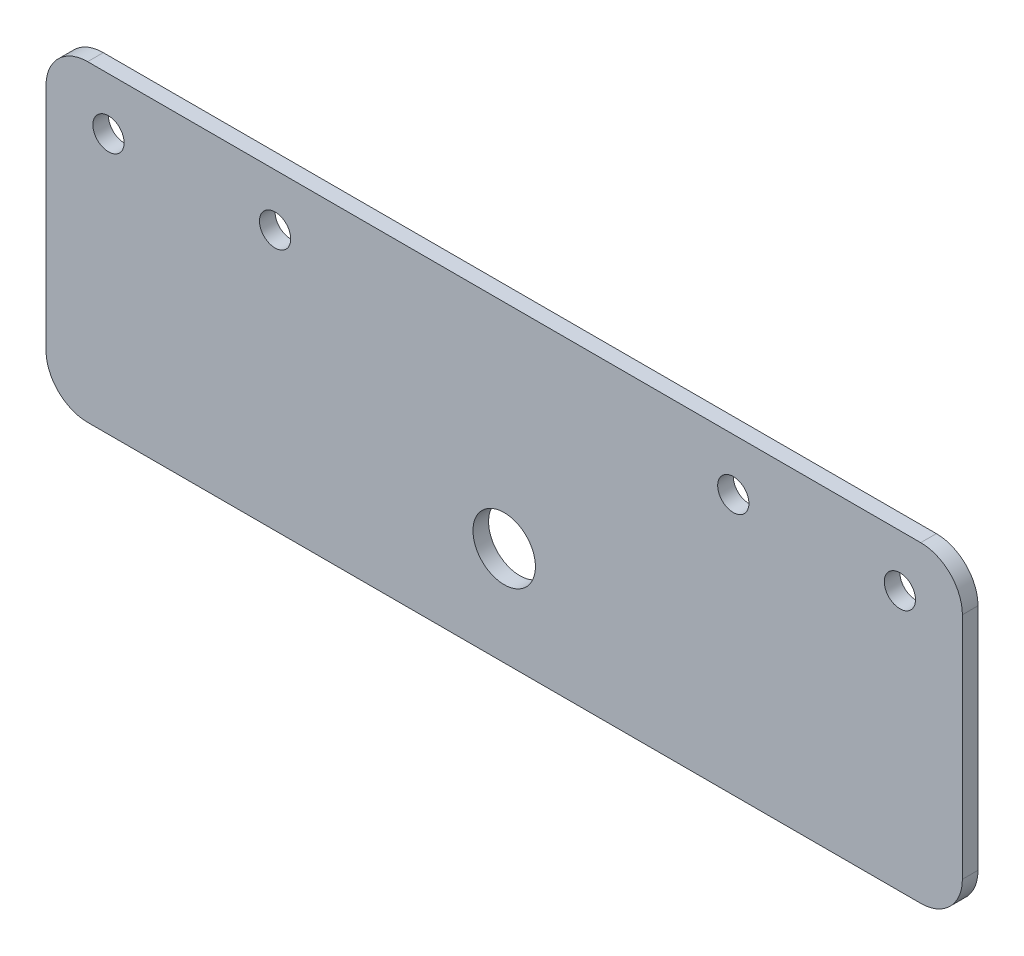
SolidWorks part; units mm, degrees
material "Hexcel AS4C (3000 丝)"
ref_plane "前视基准面" through (0, 0, 0) normal (0, 0, 1) x (1, 0, 0)
ref_plane "上视基准面" through (0, 0, 0) normal (0, 1, 0) x (1, 0, 0)
ref_plane "右视基准面" through (0, 0, 0) normal (1, 0, 0) x (0, 0, -1)
sketch "草图1" plane through (0, 0, 0) normal (0, 0, 1) x (1, 0, 0)
  line L0 (-25.8013, 1.0308) -> (-25.8013, -18.9692) construction
  line L1 (34.1987, 1.0308) -> (34.1987, -18.9692) construction
  line L2 (-25.8013, 11.0308) -> (34.1987, 11.0308)
  line L3 (-25.8013, -18.9692) -> (34.1987, -18.9692)
  line L4 (-25.8013, 11.0308) -> (-25.8013, 1.0308) construction
  line L5 (-25.8013, 1.0308) -> (34.1987, 1.0308) construction
  line L6 (34.1987, 1.0308) -> (34.1987, 11.0308) construction
  line L7 (-25.8013, 6.0308) -> (-17.8013, 6.0308) construction
  line L8 (-25.8013, 6.0308) -> (-33.8013, 6.0308) construction
  line L9 (34.1987, 6.0308) -> (26.1987, 6.0308) construction
  line L10 (34.1987, 6.0308) -> (42.1987, 6.0308) construction
  line L11 (4.1987, 1.0308) -> (4.1987, -9.4692) construction
  line L12 (-25.8013, 11.0308) -> (-35.8013, 11.0308)
  line L13 (-39.8013, 7.0308) -> (-39.8013, -14.9692)
  line L14 (-35.8013, -18.9692) -> (-25.8013, -18.9692)
  line L15 (34.1987, 11.0308) -> (44.1987, 11.0308)
  line L16 (48.1987, 7.0308) -> (48.1987, -14.9692)
  line L17 (44.1987, -18.9692) -> (34.1987, -18.9692)
  circle A1 centre (4.1987, -9.4692) radius 3
  circle A2 centre (-17.8013, 6.0308) radius 1.5
  circle A3 centre (-33.8013, 6.0308) radius 1.5
  circle A4 centre (26.1987, 6.0308) radius 1.5
  circle A5 centre (42.1987, 6.0308) radius 1.5
  arc A6 (44.1987, 11.0308) -> (48.1987, 7.0308) centre (44.1987, 7.0308) cw
  arc A7 (48.1987, -14.9692) -> (44.1987, -18.9692) centre (44.1987, -14.9692) cw
  arc A8 (-35.8013, -18.9692) -> (-39.8013, -14.9692) centre (-35.8013, -14.9692) cw
  arc A9 (-39.8013, 7.0308) -> (-35.8013, 11.0308) centre (-35.8013, 7.0308) cw
  point P4 (-25.8013, 6.0308)
  point P7 (34.1987, 6.0308)
  dimension "D1" = 4
extrude "凸台-拉伸1" add sketch "草图1" along normal blind 1.5
